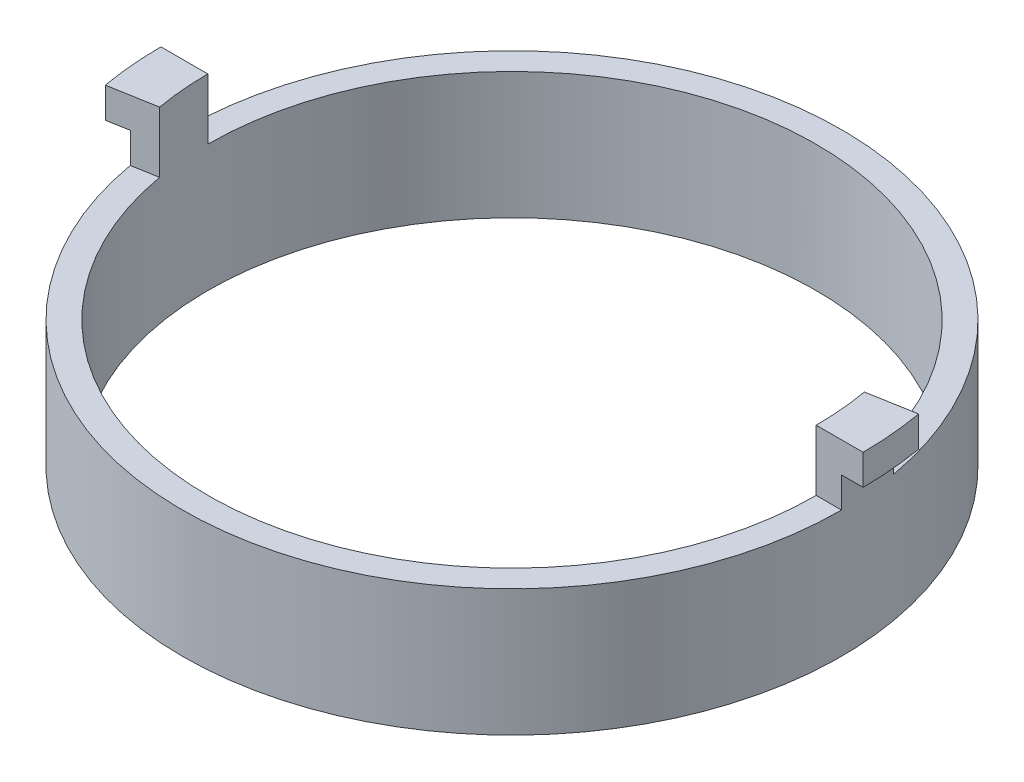
SolidWorks part; units mm, degrees
ref_plane "Front Plane" through (0, 0, 0) normal (0, 0, 1) x (1, 0, 0)
ref_plane "Top Plane" through (0, 0, 0) normal (0, 1, 0) x (1, 0, 0)
ref_plane "Right Plane" through (0, 0, 0) normal (1, 0, 0) x (0, 0, -1)
sketch "Sketch1" plane through (0, 0, 0) normal (0, 1, 0) x (1, 0, 0)
  circle A0 centre (0, 0) radius 12
  circle A1 centre (0, 0) radius 13
  dimension "D1" = 24
  dimension "D2" = 26
extrude "Boss-Extrude1" add sketch "Sketch1" along normal blind 5
sketch "Sketch2" plane through (0, 0, 0) normal (0, 0, 1) x (1, 0, 0)
  line L0 (-13, 5) -> (-12, 5)
  line L1 (-12, 5) -> (-12, 6.2)
  line L4 (-12, 7.4) -> (-13.85, 7.4)
  line L5 (-13.85, 7.4) -> (-13.85, 6.2)
  line L6 (-13.85, 6.2) -> (-13, 6.2)
  line L7 (-13, 6.2) -> (-13, 5)
  line L8 (-12.5, 5) -> (-12.5, 7.4) construction
  line L9 (0, 0) -> (0, 5)
  line L10 (-13, 0) -> (13, 0) construction
  line L11 (13, 5) -> (-13, 5) construction
  line L12 (12.5, 5) -> (12.5, 7.4) construction
  line L21 (-12, 6.2) -> (-12, 7.4)
  line L22 (12, 6.2) -> (12, 7.4)
  line L23 (13, 6.2) -> (13, 5)
  line L24 (13.85, 6.2) -> (13, 6.2)
  line L25 (13.85, 7.4) -> (13.85, 6.2)
  line L26 (12, 7.4) -> (13.85, 7.4)
  line L27 (12, 5) -> (12, 6.2)
  line L28 (13, 5) -> (12, 5)
  dimension "D1" = 1.2
  dimension "D2" = 0.85
  dimension "D3" = 1.2
revolve "Revolve1" add sketch "Sketch2" angle 10 about L9
